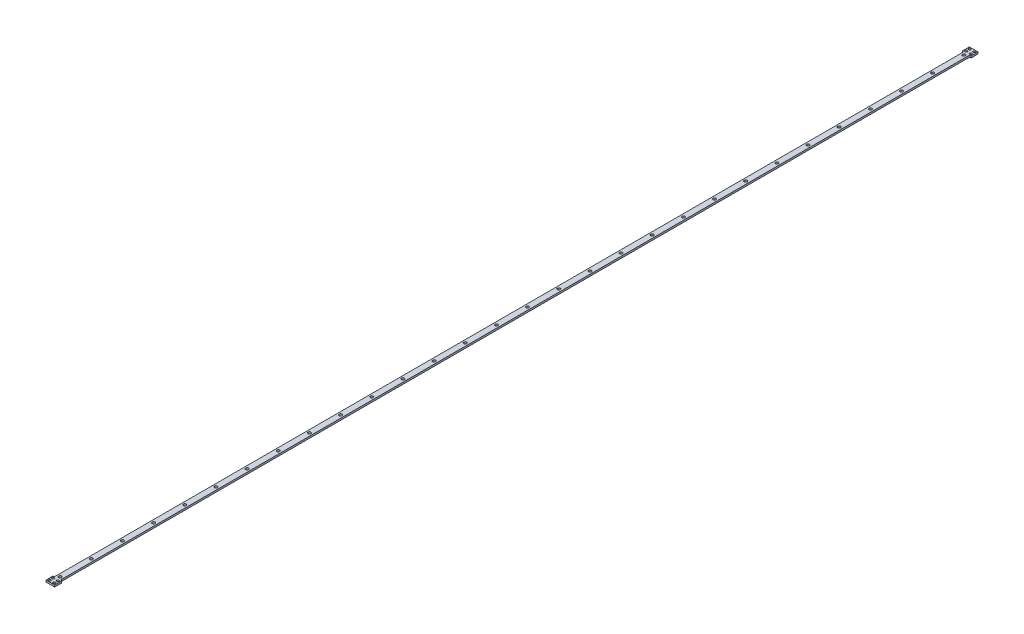
SolidWorks part; units mm, degrees
ref_plane "Front Plane" through (0, 0, 0) normal (0, 0, 1) x (1, 0, 0)
ref_plane "Top Plane" through (0, 0, 0) normal (0, 1, 0) x (1, 0, 0)
ref_plane "Right Plane" through (0, 0, 0) normal (1, 0, 0) x (0, 0, -1)
sketch "Sketch1" plane through (0, 0, 0) normal (0, 1, 0) x (1, 0, 0)
  line L0 (0, 0) -> (0, 1600)
  line L1 (0, 0) -> (15, 0)
  line L2 (0, 1600) -> (15, 1600)
  line L3 (15, 0) -> (15, 1600)
  line L4 (2.5, 14.5) -> (2.5, 1585.5)
  line L5 (12.5, 1585.5) -> (12.5, 14.5)
  circle A0 centre (0, 14.5) radius 2.5
  circle A1 centre (15, 14.5) radius 2.5
  circle A2 centre (0, 1585.5) radius 2.5
  circle A3 centre (15, 1585.5) radius 2.5
  dimension "D1" = 5
  dimension "Rail Length" = 1600
  dimension "Rail Width" = 15
  dimension "D2" = 14.5
  dimension "D4" = 14.5
  dimension "D3" = 14.5
  dimension "D5" = 14.5
extrude "Boss-Extrude1" add sketch "Sketch1" along normal blind 3.2 contours A3 L3 L2 L0 A2 L4 A0 L1 A1 L5
sketch "Sketch2" plane through (0, 3.2, 0) normal (0, 1, 0) x (1, 0, 0)
  line L0 (3.5, 9) -> (3.5, 3) construction
  line L1 (3.5, 3) -> (11.5, 3) construction
  line L2 (11.5, 3) -> (11.5, 9) construction
  line L3 (11.5, 9) -> (3.5, 9) construction
  line L4 (7.5, 17) -> (7.5, 0)
  line L5 (7.5, 1597) -> (7.5, 1600)
  line L10 (3.5, 1597) -> (11.5, 1597) construction
  line L11 (11.5, 1597) -> (11.5, 1591) construction
  line L12 (11.5, 1591) -> (3.5, 1591) construction
  line L13 (3.5, 1591) -> (3.5, 1597) construction
  line L23 (15, 1588) -> (15, 1600)
  line L24 (15, 1600) -> (0, 1600)
  line L25 (0, 1600) -> (0, 1588)
  line L26 (2.5, 1585.5) -> (2.5, 14.5)
  line L27 (0, 12) -> (0, 0)
  line L28 (0, 0) -> (15, 0)
  line L29 (15, 0) -> (15, 12)
  line L30 (12.5, 14.5) -> (12.5, 1585.5)
  line L31 (15, 1588) -> (15, 1600)
  line L32 (15, 1600) -> (0, 1600)
  line L33 (0, 1600) -> (0, 1588)
  line L34 (2.5, 1585.5) -> (2.5, 14.5)
  line L35 (0, 12) -> (0, 0)
  line L36 (0, 0) -> (15, 0)
  line L37 (15, 0) -> (15, 12)
  line L38 (12.5, 14.5) -> (12.5, 1585.5)
  circle A0 centre (7.5, 17) radius 2.5
  arc A5 (15, 1588) -> (12.5, 1585.5) centre (15, 1585.5) ccw
  arc A6 (2.5, 1585.5) -> (0, 1588) centre (0, 1585.5) ccw
  arc A7 (0, 12) -> (2.5, 14.5) centre (0, 14.5) ccw
  arc A8 (12.5, 14.5) -> (15, 12) centre (15, 14.5) ccw
  arc A9 (15, 1588) -> (12.5, 1585.5) centre (15, 1585.5) ccw
  arc A10 (2.5, 1585.5) -> (0, 1588) centre (0, 1585.5) ccw
  arc A11 (0, 12) -> (2.5, 14.5) centre (0, 14.5) ccw
  arc A12 (12.5, 14.5) -> (15, 12) centre (15, 14.5) ccw
  point P0 (3.5, 3)
  point P1 (11.5, 3)
  point P2 (11.5, 9)
  point P3 (3.5, 9)
  point P11 (7.5, 3)
  point P15 (3.5, 1597)
  point P18 (11.5, 1597)
  point P19 (11.5, 1591)
  point P20 (3.5, 1591)
  point P26 (7.5, 1597)
  point P31 (7.5, 17)
  dimension "D8" = 5
  dimension "D1" = 8
  dimension "D2" = 6
  dimension "D4" = 8
  dimension "D5" = 6
  dimension "D3" = 3
  dimension "D7" = 17
  dimension "D6" = 3
  dimension "D9" = 0
extrude "Cut-Extrude1" cut sketch "Sketch2" against normal through all
hole_wizard "Ø4.0mm Dowel Hole1" positions "3DSketch3" profile "Sketch5" hole size "Ø4.0" standard "ISO" end condition through all
sketch3d "3DSketch3"
  point P0 (11.5, 3.2, -1591)
  point P3 (3.5, 3.2, -1591)
  point P6 (3.5, 3.2, -1597)
  point P9 (11.5, 3.2, -1597)
  point P12 (3.5, 3.2, -9)
  point P15 (3.5, 3.2, -3)
  point P18 (11.5, 3.2, -9)
  point P21 (11.5, 3.2, -3)
sketch "Sketch5" plane through (11.5, 3.2, -1591) normal (1, 0, 0) x (0, 0, 1)
  line L0 (0, 0) -> (0, 3.2)
  line L1 (0, 3.2) -> (2, 3.2)
  line L2 (2, 3.2) -> (2, 0.025)
  line L3 (2, 0.025) -> (2.025, 0)
  line L5 (2.025, 0) -> (0, 0)
  line L6 (-2, 0.025) -> (-2.025, 0) construction
  line L11 (0, -6.35) -> (0, 107.95) construction
  dimension "Thru Hole Dia." = 4
  dimension "Thru Hole Depth" = 3.2
  dimension "Near C'Sink Dia." = 4.05
  dimension "Near C'Sink Angle" = 90
pattern_linear "LPattern2" count 30 spacing 54 along (0, 0, -1) of "Cut-Extrude1"
equation "\"Rail Length\"= 1600"
equation "\"Rail Width\"= 15"
equation "\"Rail Thickness\"= 3.2"
equation "\"Rail Length@Sketch1\"= \"Rail Length\""
equation "\"Rail Width@Sketch1\"= \"Rail Width\""
equation "\"Feature Hole Offset Distance\"= 3"
equation "\"Feat. Hole Horiz. Spacing\"= 8"
equation "\"D1@Sketch2\"= \"Feat. Hole Horiz. Spacing\""
equation "\"D4@Sketch2\"= \"Feat. Hole Horiz. Spacing\""
equation "\"Feat. Hole Vert. Spacing\"= 6"
equation "\"D2@Sketch2\"= \"Feat. Hole Vert. Spacing\""
equation "\"D5@Sketch2\"= \"Feat. Hole Vert. Spacing\""
equation "\"Inter. Hole Size\"= 5"
equation "\"Feat. Hole Size\"= 4"
equation "\"D8@Sketch2\"= \"Inter. Hole Size\""
equation "\"No. Inter. Hole\"= 30"
equation "\"D1@LPattern2\"= \"No. Inter. Hole\""
equation "\"D3@LPattern2\"= ( \"Rail Length\" - ( 2 * \"D7@Sketch2\" ) ) / ( \"No. Inter. Hole\" - 1 )"
equation "\"Narrow Width\"= 10"
equation "\"D1@Sketch1\"= \"Rail Width\" - \"Narrow Width\""
equation "\"D1@Boss-Extrude1\"= \"Rail Thickness\""
equation "\"D3@Sketch2\"= \"Feature Hole Offset Distance\""
equation "\"D7@Sketch2\"= ( 2 * \"Feature Hole Offset Distance\" ) + \"Feat. Hole Vert. Spacing\" + \"Inter. Hole Size\""
equation "\"D6@Sketch2\"= \"Feature Hole Offset Distance\""
equation "\"D2@Sketch1\"= ( 2 * \"Feature Hole Offset Distance\" ) + \"Feat. Hole Vert. Spacing\" + ( \"D1@Sketch1\" / 2 )"
equation "\"D4@Sketch1\"= \"D2@Sketch1\""
equation "\"D3@Sketch1\"= \"D2@Sketch1\""
equation "\"D5@Sketch1\"= \"D2@Sketch1\""
